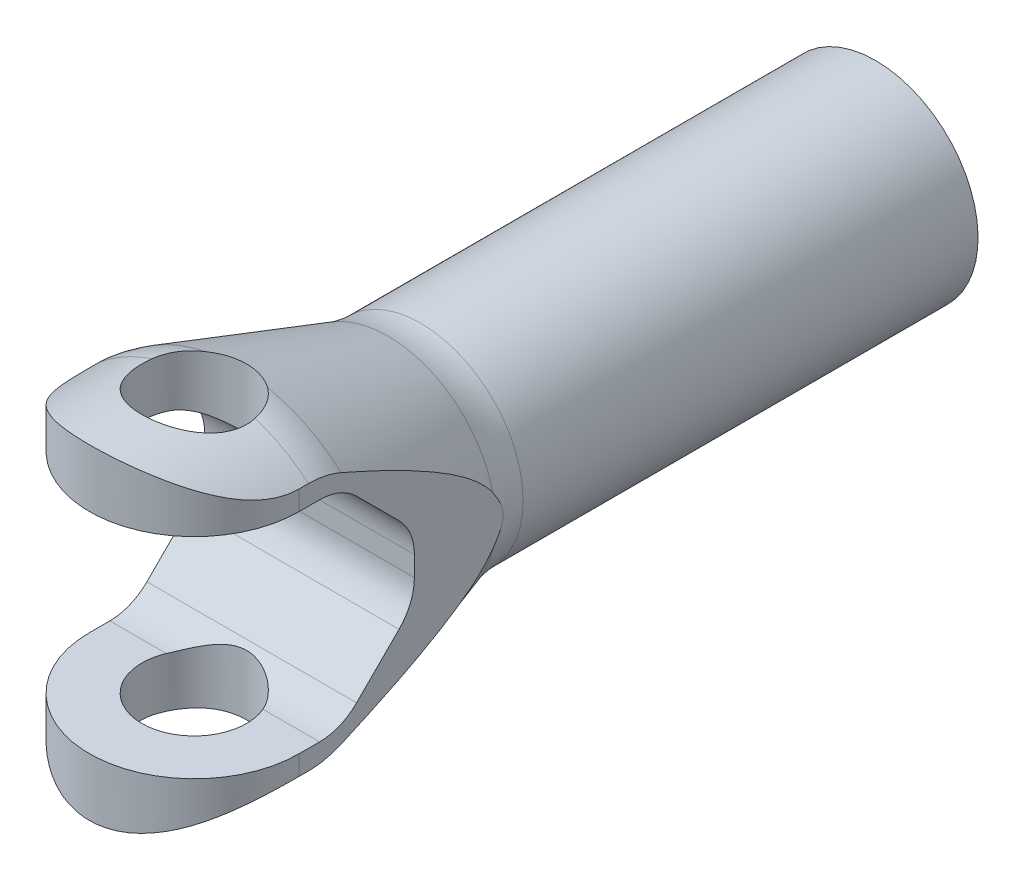
SolidWorks part; units mm, degrees
ref_plane "Front Plane" through (0, 0, 0) normal (0, 0, 1) x (1, 0, 0)
ref_plane "Top Plane" through (0, 0, 0) normal (0, 1, 0) x (1, 0, 0)
ref_plane "Right Plane" through (0, 0, 0) normal (1, 0, 0) x (0, 0, -1)
sketch "Sketch1" plane through (0, 0, 0) normal (1, 0, 0) x (0, 0, -1)
  line L0 (0, 31.0481) -> (0, 0)
  line L1 (0, 31.0481) -> (21.794, 31.0481)
  line L2 (28.0454, 30.0459) -> (56.9546, 20.5331)
  line L3 (63.206, 19.531) -> (150, 19.531)
  line L4 (150, 19.531) -> (150, 0)
  line L5 (150, 0) -> (0, 0)
  arc A0 (56.9546, 20.5331) -> (63.206, 19.531) centre (63.206, 39.531) ccw
  arc A1 (21.794, 31.0481) -> (28.0454, 30.0459) centre (21.794, 11.0481) cw
  point P9 (60, 19.531)
  point P12 (25, 31.0481)
  dimension "D4" = 20
  dimension "D1" = 25
  dimension "D2" = 60
  dimension "D3" = 150
revolve "Revolve1" add sketch "Sketch1" angle 360 about L5
sketch "Sketch2" plane through (0, 0, 0) normal (1, 0, 0) x (0, 0, -1)
  line L0 (0, 20) -> (0, -20)
  line L1 (0, 31.0481) -> (0, -31.0481) construction
  line L3 (0, 20) -> (23.9033, 20)
  line L4 (28.0454, 30.0459) -> (28.0454, -30.0459) construction
  line L5 (30.9743, 17.0711) -> (39.0711, 8.9743)
  line L6 (42, 1.9033) -> (42, -1.9033)
  line L7 (39.0711, -8.9743) -> (30.9743, -17.0711)
  line L8 (23.9033, -20) -> (0, -20)
  arc A0 (30.9743, -17.0711) -> (23.9033, -20) centre (23.9033, -10) cw
  arc A1 (42, -1.9033) -> (39.0711, -8.9743) centre (32, -1.9033) cw
  arc A2 (39.0711, 8.9743) -> (42, 1.9033) centre (32, 1.9033) cw
  arc A3 (23.9033, 20) -> (30.9743, 17.0711) centre (23.9033, 10) cw
  point P5 (0, 0)
  point P14 (28.0454, -20)
  point P21 (28.0454, 20)
  dimension "D4" = 10
  dimension "D1" = 40
  dimension "D2" = 42
  dimension "D3" = 135
extrude "Cut-Extrude1" cut sketch "Sketch2" against normal through all both and the other way through all
sketch "Sketch3" plane through (0, 0, 0) normal (0, 1, 0) x (1, 0, 0)
  line L0 (-20, 20) -> (-20, 58.9001)
  line L1 (20, 20) -> (20, 58.9001)
  line L2 (-20, 58.9001) -> (20, 58.9001)
  line L3 (20, 58.9001) -> (30.5964, 58.9001)
  line L4 (30.5964, 58.9001) -> (30.5964, 0)
  line L5 (30.5964, 0) -> (0, 0)
  line L6 (-20, 58.9001) -> (-33.9674, 58.9001)
  line L7 (-33.9674, 58.9001) -> (-33.9674, 0)
  line L8 (-33.9674, 0) -> (0, 0)
  arc A0 (-20, 20) -> (20, 20) centre (0, 20) ccw
  arc A1 (19.531, 63.206) -> (20.5331, 56.9546) centre (39.531, 63.206) ccw construction
  arc A2 (-20.5331, 56.9546) -> (-19.531, 63.206) centre (-39.531, 63.206) ccw construction
  dimension "D1" = 20
extrude "Cut-Extrude3" cut sketch "Sketch3" against normal through all both and the other way through all contours A0 L0 L6 L7 L8 | A0 L5 L4 L3 L1
sketch "Sketch4" plane through (0, 0, 0) normal (0, 1, 0) x (1, 0, 0)
  circle A0 centre (0, 20) radius 10
  dimension "D1" = 20
extrude "Cut-Extrude4" cut sketch "Sketch4" against normal through all both and the other way through all
